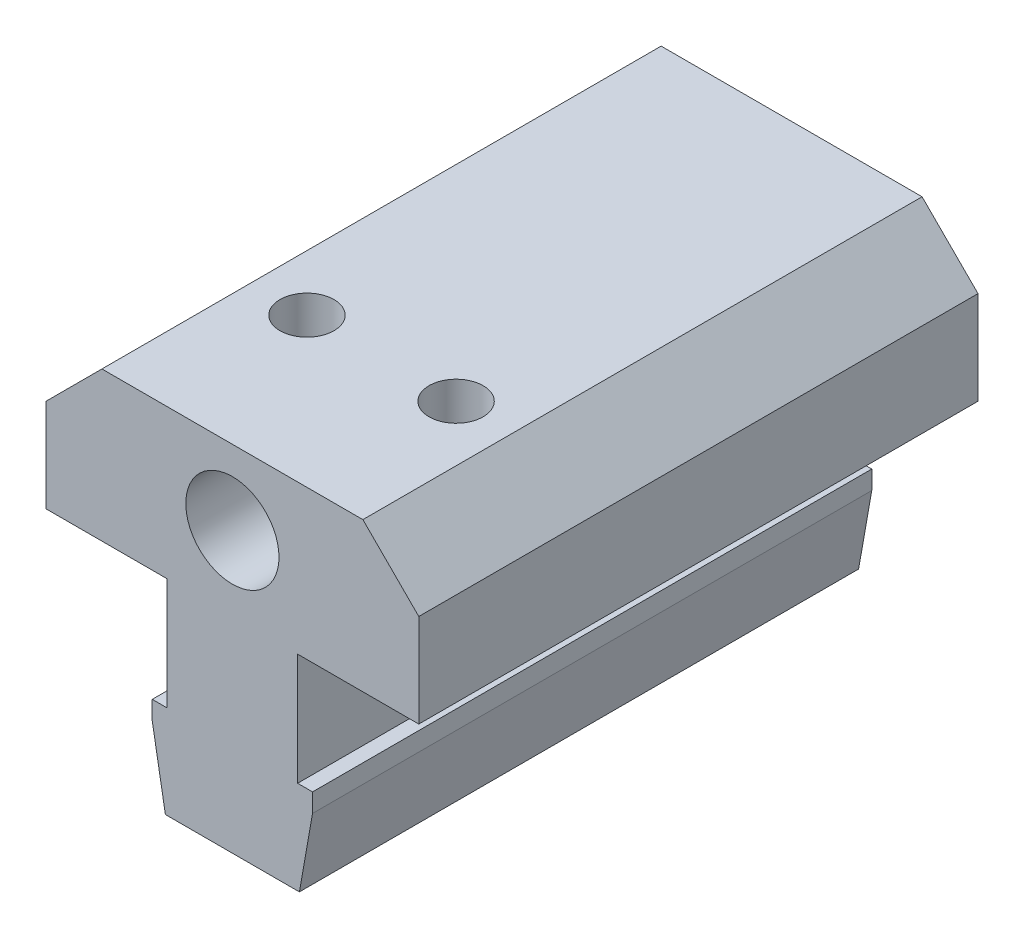
SolidWorks part; units mm, degrees
ref_plane "Front Plane" through (0, 0, 0) normal (0, 0, 1) x (1, 0, 0)
ref_plane "Top Plane" through (0, 0, 0) normal (0, 1, 0) x (1, 0, 0)
ref_plane "Right Plane" through (0, 0, 0) normal (1, 0, 0) x (0, 0, -1)
sketch "Sketch1" plane through (0, 0, 0) normal (0, 0, 1) x (1, 0, 0)
  line L0 (0, 0) -> (20, 0)
  line L1 (20, 0) -> (20, -8)
  line L2 (20, -8) -> (13.5, -8)
  line L3 (13.5, -8) -> (13.5, -14)
  line L4 (13.5, -14) -> (14.3, -14)
  line L5 (14.3, -14) -> (14.3, -19)
  line L6 (14.3, -19) -> (5.7, -19)
  line L7 (5.7, -19) -> (5.7, -14)
  line L8 (5.7, -14) -> (6.5, -14)
  line L9 (6.5, -14) -> (6.5, -8)
  line L10 (6.5, -8) -> (0, -8)
  line L11 (0, -8) -> (0, 0)
  point P14 (6.5, -11)
  dimension "D1" = 20
  dimension "D2" = 6
  dimension "D3" = 5
  dimension "D4" = 8
  dimension "D5" = 7
  dimension "D6" = 0.8
extrude "Boss-Extrude1" add sketch "Sketch1" along normal blind 30
sketch "Sketch2" plane through (0, 0, 0) normal (0, 1, 0) x (1, 0, 0)
  line L0 (0, -30) -> (0, 0) construction
  line L2 (20, -30) -> (20, 0) construction
  circle A0 centre (14, -22) radius 1.45
  circle A1 centre (6, -22) radius 1.45
  dimension "D3" = 2.9
  dimension "D1" = 14
  dimension "D2" = 8
  dimension "D4" = 14
extrude "Cut-Extrude1" cut sketch "Sketch2" against normal blind 8
sketch "Sketch3" plane through (0, 0, 30) normal (0, 0, 1) x (1, 0, 0)
  line L0 (20, 0) -> (0, 0) construction
  line L1 (20, -8) -> (20, 0) construction
  circle A0 centre (10, -4) radius 2.5
  dimension "D1" = 5
  dimension "D2" = 4
  dimension "D3" = 10
extrude "Cut-Extrude2" cut sketch "Sketch3" against normal through all
chamfer "Chamfer1" distance 3 distance2 3 2 edges at (20, 0, 15) (0, 0, 15)
chamfer "Chamfer2" distance 4 angle 10 2 edges at (14.3, -19, 15) (5.7, -19, 15)
